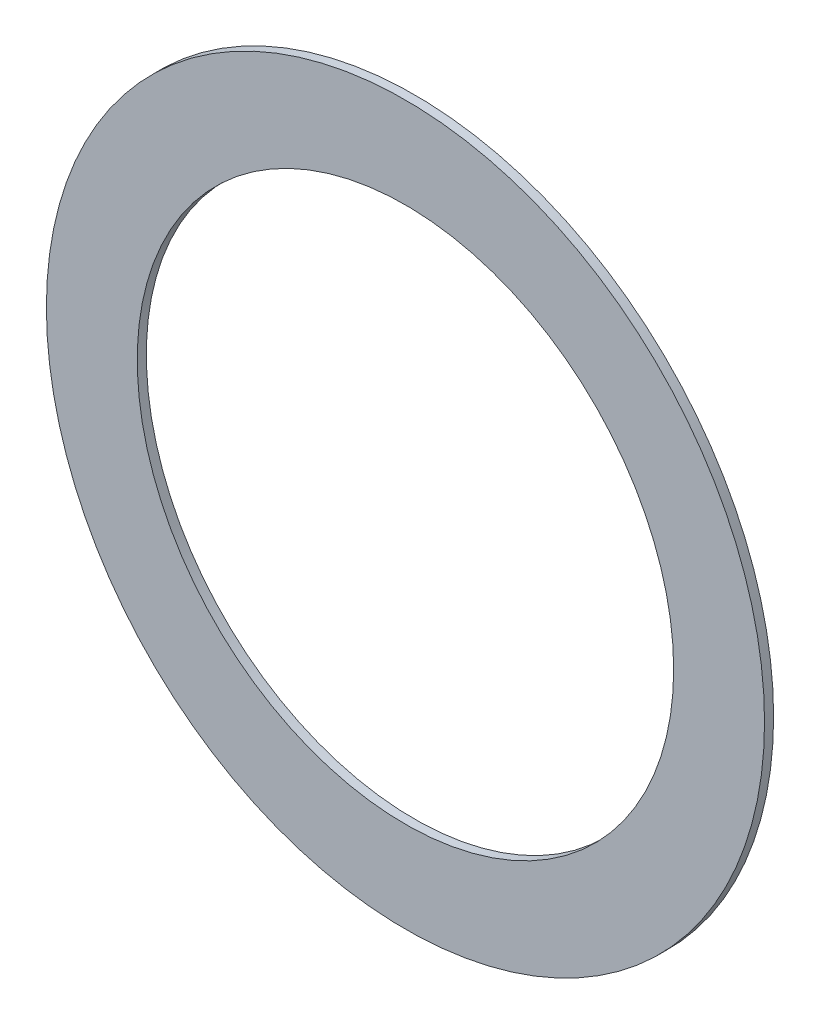
SolidWorks part; units mm, degrees
ref_plane "Front Plane" through (0, 0, 0) normal (0, 0, 1) x (1, 0, 0)
ref_plane "Top Plane" through (0, 0, 0) normal (0, 1, 0) x (1, 0, 0)
ref_plane "Right Plane" through (0, 0, 0) normal (1, 0, 0) x (0, 0, -1)
sketch "Sketch1" plane through (0, 0, 0) normal (0, 0, 1) x (1, 0.0097, 0)
  circle A0 centre (-34.407, 7.3011) radius 29.522
  circle A2 centre (-34.407, 7.3011) radius 39.522
  dimension "D1" = 59.044
  dimension "D2" = 79.044
extrude "Boss-Extrude2" add sketch "Sketch1" along normal blind 1
